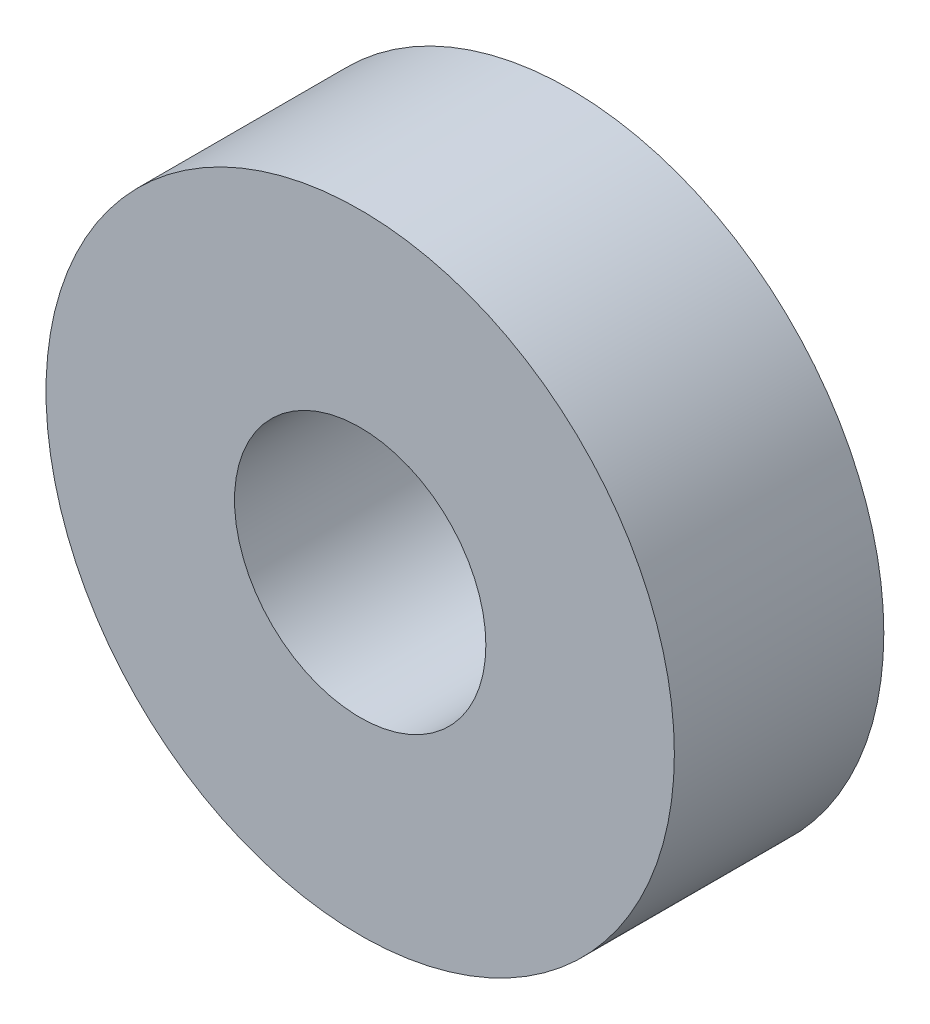
SolidWorks part; units mm, degrees
material "Copper"
ref_plane "Front Plane" through (0, 0, 0) normal (0, 0, 1) x (1, 0, 0)
ref_plane "Top Plane" through (0, 0, 0) normal (0, 1, 0) x (1, 0, 0)
ref_plane "Right Plane" through (0, 0, 0) normal (1, 0, 0) x (0, 0, -1)
sketch "Sketch1" plane through (0, 0, 0) normal (0, 0, 1) x (1, 0, 0)
  circle A0 centre (0, 0) radius 15
  circle A1 centre (0, 0) radius 6
  dimension "D1" = 30
  dimension "D2" = 12
extrude "Boss-Extrude1" add sketch "Sketch1" along normal blind 10
